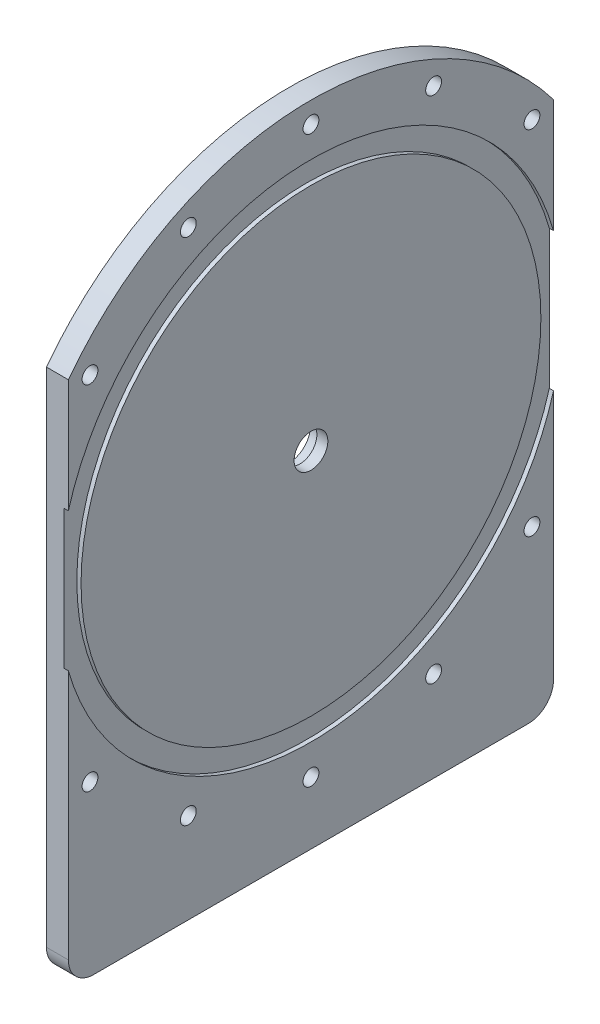
SolidWorks part; units mm, degrees
material "6061 Alloy"
ref_plane "Front Plane" through (0, 0, 0) normal (0, 0, 1) x (1, 0, 0)
ref_plane "Top Plane" through (0, 0, 0) normal (0, 1, 0) x (1, 0, 0)
ref_plane "Right Plane" through (0, 0, 0) normal (1, 0, 0) x (0, 0, -1)
sketch "Sketch1" plane through (0, 0, 0) normal (1, 0, 0) x (0, 0, -1)
  line L0 (0, -1000) -> (0, 49000) construction
  line L1 (5.5562, 0) -> (2.7781, 4.8119) construction
  line L2 (2.7781, 4.8119) -> (-2.7781, 4.8119) construction
  line L3 (-2.7781, 4.8119) -> (-5.5562, 0) construction
  line L4 (-5.5562, 0) -> (-2.7781, -4.8119) construction
  line L5 (-2.7781, -4.8119) -> (2.7781, -4.8119) construction
  line L6 (2.7781, -4.8119) -> (5.5562, 0) construction
  line L7 (-65.405, -103.8551) -> (65.405, -103.8551)
  line L8 (-73.025, -96.2351) -> (-73.025, -69.997)
  line L10 (73.025, -96.2351) -> (73.025, -69.997)
  circle A0 centre (0, 0) radius 69.85 construction
  circle A1 centre (0, 0) radius 76.2 construction
  circle A2 centre (0, 0) radius 5.08
  circle A3 centre (0, 0) radius 3.9688 construction
  arc A4 (79.6018, -44.9981) -> (-79.6018, -44.9981) centre (0, 0) ccw
  circle A5 centre (0, 0) radius 11.5094 construction
  circle A6 centre (0, 0) radius 91.44 construction
  arc A7 (65.405, -103.8551) -> (73.025, -96.2351) centre (65.405, -96.2351) ccw
  arc A8 (-65.405, -103.8551) -> (-73.025, -96.2351) centre (-65.405, -96.2351) cw
  arc A9 (79.6018, -44.9981) -> (73.025, -69.997) centre (123.825, -69.997) ccw
  arc A10 (-73.025, -69.997) -> (-79.6018, -44.9981) centre (-123.825, -69.997) ccw
  point P19 (73.025, -103.8551)
  point P26 (-73.025, -103.8551)
  dimension "D1" = 152.4
  dimension "D2" = 139.7
  dimension "D3" = 10.16
  dimension "D4" = 7.9375
  dimension "D5" = 15.24
  dimension "D6" = 23.0188
  dimension "D8" = 7.62
  dimension "D9" = 50.8
  dimension "D7" = 146.05
extrude "Boss-Extrude1" add sketch "Sketch1" along normal blind 6.604
sketch "Sketch2" plane through (0, 0, 0) normal (1, 0, 0) x (0, 0, -1)
  circle A0 centre (0, 0) radius 6.35 construction
  circle A1 centre (0, 0) radius 6.477
  dimension "D1" = 12.7
  dimension "D2" = 12.954
extrude "Cut-Extrude1" cut sketch "Sketch2" along direction (1, 0, 0) on the side of the normal blind 3.302
sketch "Sketch3" plane through (6.604, 0, 0) normal (1, 0, 0) x (0, 0, -1)
  circle A0 centre (0, 0) radius 75.946
  circle A1 centre (0, 0) radius 69.215
  dimension "D2" = 138.43
  dimension "D1" = 6.731
extrude "Cut-Extrude2" cut sketch "Sketch3" against normal blind 1.27
sketch "Sketch4" plane through (0, 0, 0) normal (-1, 0, 0) x (0, 0, 1)
  line L0 (0, -1000) -> (0, 49000) construction
  line L1 (-1000, 0) -> (49000, 0) construction
  circle A0 centre (-82.9566, 18.9343) radius 2.3812
  circle A1 centre (0, 85.09) radius 2.3812
  circle A2 centre (-66.526, 53.0527) radius 2.3812
  circle A3 centre (0, 0) radius 85.09 construction
  circle A4 centre (36.9192, 76.6634) radius 2.3813
  circle A5 centre (66.526, 53.0527) radius 2.3813
  circle A6 centre (82.9566, 18.9343) radius 2.3812
  circle A7 centre (82.9566, -18.9343) radius 2.3813
  circle A8 centre (66.526, -53.0527) radius 2.3812
  circle A9 centre (36.9192, -76.6634) radius 2.3812
  circle A10 centre (0, -85.09) radius 2.3812
  circle A11 centre (-36.9192, -76.6634) radius 2.3812
  circle A12 centre (-66.526, -53.0527) radius 2.3812
  circle A13 centre (-82.9566, -18.9343) radius 2.3813
  circle A14 centre (-36.9192, 76.6634) radius 2.3812
  point P34 (0, 0)
  dimension "D2" = 14
extrude "Cut-Extrude3" cut sketch "Sketch4" against normal through all
sketch "Sketch5" plane through (0, 0, 0) normal (-1, 0, 0) x (0, 0, 1)
  circle A0 centre (0, 85.09) radius 3.7783
  circle A1 centre (-82.9566, 18.9343) radius 3.7783
  circle A2 centre (-66.526, 53.0527) radius 3.7783
  circle A3 centre (36.9192, 76.6634) radius 3.7783
  circle A5 centre (-36.9192, 76.6634) radius 3.7783
  circle A6 centre (66.526, 53.0527) radius 3.7783
  circle A7 centre (82.9566, 18.9343) radius 3.7783
  circle A8 centre (82.9566, -18.9343) radius 3.7783
  circle A9 centre (66.526, -53.0527) radius 3.7783
  circle A10 centre (36.9192, -76.6634) radius 3.7783
  circle A11 centre (0, -85.09) radius 3.7783
  circle A12 centre (-36.9192, -76.6634) radius 3.7783
  circle A13 centre (-66.526, -53.0527) radius 3.7783
  circle A14 centre (-82.9566, -18.9343) radius 3.7783
  point P29 (0, 0)
  dimension "D1" = 14
extrude "Cut-Extrude4" cut sketch "Sketch5" against normal blind 1.27
sketch "Sketch6" plane through (6.604, 0, 0) normal (1, 0, 0) x (0, 0, -1)
  line L0 (-73.025, -69.997) -> (-73.025, 55.0329)
  line L1 (-73.025, 55.0329) -> (-110.5376, 55.0329)
  line L2 (-110.5376, 55.0329) -> (-110.5376, -69.997)
  line L3 (-110.5376, -69.997) -> (-73.025, -69.997)
  line L4 (73.025, -69.997) -> (73.025, 55.0329)
  line L5 (73.025, 55.0329) -> (102.9616, 55.0329)
  line L6 (102.9616, 55.0329) -> (102.9616, -69.997)
  line L7 (102.9616, -69.997) -> (73.025, -69.997)
  arc A1 (79.6018, -44.9981) -> (-79.6018, -44.9981) centre (0, 0) ccw construction
extrude "Cut-Extrude6" cut sketch "Sketch6" against normal through all contours L1 L2 L3 L0 | L5 L6 L7 L4
